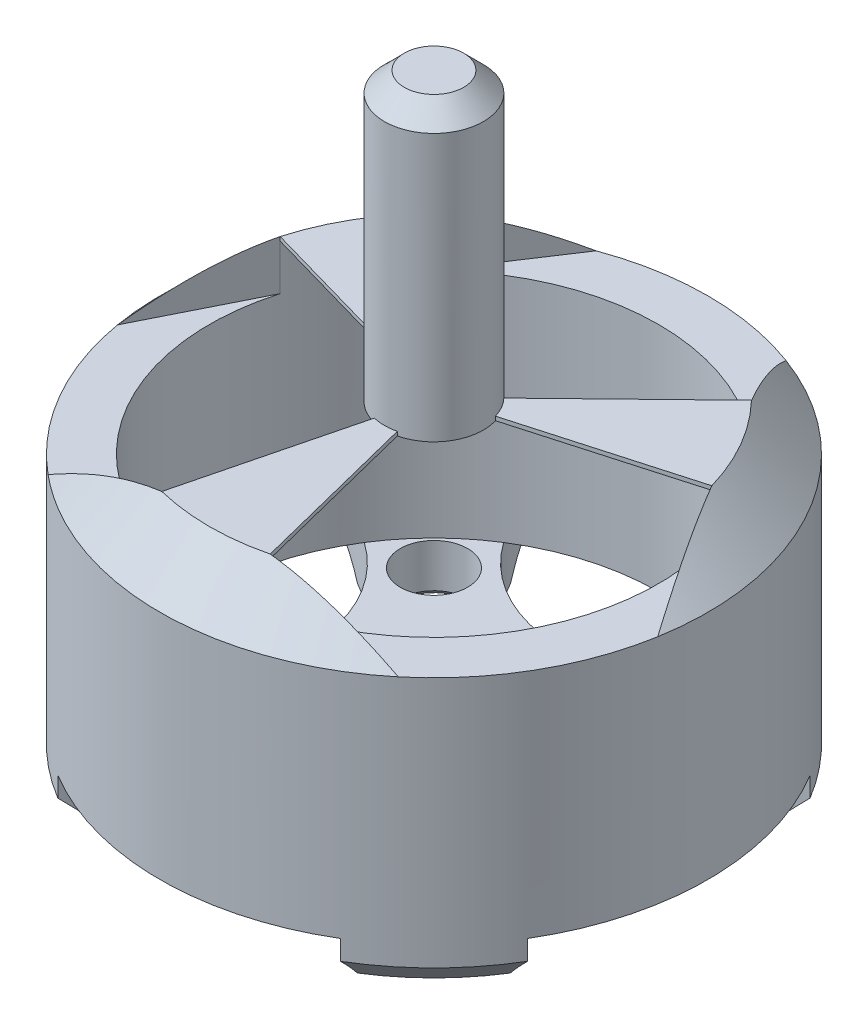
SolidWorks part; units mm, degrees
ref_plane "Front Plane" through (0, 0, 0) normal (0, 0, 1) x (1, 0, 0)
ref_plane "Top Plane" through (0, 0, 0) normal (0, 1, 0) x (1, 0, 0)
ref_plane "Right Plane" through (0, 0, 0) normal (1, 0, 0) x (0, 0, -1)
sketch "Sketch1" plane through (0, 0, 0) normal (0, 0, 1) x (1, 0, 0)
  line L0 (0, 41.0205) -> (0, -14.1146) construction
  line L1 (0, 0) -> (-1, 0)
  line L2 (-1, 0) -> (-1, 1)
  line L3 (-1, 1) -> (-12.35, 1)
  line L4 (-13.85, 2.5) -> (-13.85, 15.2)
  line L5 (-11.35, 17.7) -> (-2.5, 17.7)
  line L6 (-2.5, 17.7) -> (-2.5, 31)
  line L7 (-1.5, 32) -> (0, 32)
  line L8 (0, 32) -> (0, 0)
  line L9 (-13.85, 15.2) -> (-11.35, 17.7)
  line L10 (-12.35, 1) -> (-13.85, 2.5)
  line L11 (-2.5, 31) -> (-1.5, 32)
  point P7 (-13.85, 1)
  point P8 (-13.85, 17.7)
  point P10 (-2.5, 32)
  dimension "D1" = 5
  dimension "D2" = 2
  dimension "D3" = 27.7
  dimension "D4" = 1
  dimension "D5" = 16.7
  dimension "D6" = 14.3
revolve "Revolve1" add sketch "Sketch1" angle 360 about L0
ref_plane "Plane1" through (0, 3.5, 0) normal (0, 1, 0) x (1, 0, 0)
sketch "Sketch2" plane through (0, 3.5, 0) normal (0, 1, 0) x (1, 0, 0)
  circle A0 centre (0, 0) radius 11.35
  dimension "D1" = 22.7
extrude "Cut-Extrude1" cut sketch "Sketch2" along normal blind 14
sketch "Sketch3" plane through (0, 3.5, 0) normal (0, 1, 0) x (1, 0, 0)
  circle A0 centre (0, -13.85) radius 7.4142
  circle A1 centre (0, 0) radius 13.85 construction
  dimension "D1" = 14.8285
extrude "Cut-Extrude2" cut sketch "Sketch3" against normal through all
pattern_circular "CirPattern1" count 4 over 360 about axis through (0, 0, 0) along (0, 1, 0) of "Cut-Extrude2"
sketch "Sketch6" plane through (0, 0, 0) normal (0, 1, 0) x (1, 0, 0)
  line L0 (-9.7934, -9.7934) -> (9.7934, 9.7934) construction
  line L2 (9.7934, -9.7934) -> (-9.7934, 9.7934) construction
hole_wizard "CSK for M3 Countersunk Flat Head1" positions "Sketch7" profile "Sketch8" countersink size "M3" standard "BSI"
sketch "Sketch7" plane through (0, 1, 0) normal (0, -1, 0) x (-1, 0, 0)
  line L0 (9.7934, -9.7934) -> (-9.7934, 9.7934) construction
  point P0 (5.6569, -5.6569)
  point P4 (-5.6569, 5.6569)
  dimension "D1" = 16
  dimension "D2" = 8
sketch "Sketch8" plane through (-5.6569, 1, 5.6569) normal (1, 0, 0) x (0, 0, -1)
  line L0 (0, 0) -> (0, 2.5)
  line L1 (0, 2.5) -> (1.7, 2.5)
  line L2 (1.7, 2.5) -> (1.7, 0.3)
  line L3 (1.7, 0.3) -> (2, 0)
  line L5 (2, 0) -> (0, 0)
  line L6 (-1.7, 0.3) -> (-2, 0) construction
  line L11 (0, -6.35) -> (0, 107.95) construction
  dimension "Thru Hole Dia." = 3.4
  dimension "Thru Hole Depth" = 2.5
  dimension "Near C'Sink Dia." = 4
  dimension "Near C'Sink Angle" = 90
hole_wizard "CSK for M3 Countersunk Flat Head3" positions "Sketch15" profile "Sketch14" countersink size "M3" standard "BSI"
sketch "Sketch15" plane through (0, 1, 0) normal (0, -1, 0) x (-1, 0, 0)
  line L0 (-9.7934, -9.7934) -> (9.7934, 9.7934) construction
  point P0 (6.7175, 6.7175)
  point P2 (-6.7175, -6.7175)
  dimension "D1" = 19
  dimension "D2" = 9.5
sketch "Sketch14" plane through (-6.7175, 1, -6.7175) normal (1, 0, 0) x (0, 0, -1)
  line L0 (0, 0) -> (0, 2.5)
  line L1 (0, 2.5) -> (1.7, 2.5)
  line L2 (1.7, 2.5) -> (1.7, 0.3)
  line L3 (1.7, 0.3) -> (2, 0)
  line L5 (2, 0) -> (0, 0)
  line L6 (-1.7, 0.3) -> (-2, 0) construction
  line L11 (0, -6.35) -> (0, 107.95) construction
  dimension "Thru Hole Dia." = 3.4
  dimension "Thru Hole Depth" = 2.5
  dimension "Near C'Sink Dia." = 4
  dimension "Near C'Sink Angle" = 90
ref_plane "Plane3" through (0, 17.7, 0) normal (0, 1, 0) x (1, 0, 0)
sketch "Sketch16" plane through (0, 17.7, 0) normal (0, 1, 0) x (1, 0, 0)
  line L0 (-4.7958, 12.9932) -> (-8.1694, 7.8793)
  line L1 (-8.1694, 7.8793) -> (-1.8159, 1.7183)
  line L2 (4.7958, 12.9932) -> (8.1694, 7.8793)
  line L3 (8.1694, 7.8793) -> (1.8159, 1.7183)
  line L7 (-4.7958, 12.9932) -> (0, 16.8971)
  line L8 (0, 16.8971) -> (4.7958, 12.9932)
  arc A0 (1.8159, 1.7183) -> (-1.8159, 1.7183) centre (0, 0) ccw
  circle A6 centre (0, 0) radius 13.85 construction
  circle A7 centre (0, 0) radius 11.35 construction
  circle A8 centre (0, 0) radius 2.5 construction
  dimension "D1" = 16.3388
extrude "Cut-Extrude4" cut sketch "Sketch16" against normal blind 2.5
pattern_circular "CirPattern2" count 3 over 360 about axis through (0, 0, 0) along (0, 1, 0) of "Cut-Extrude4"
